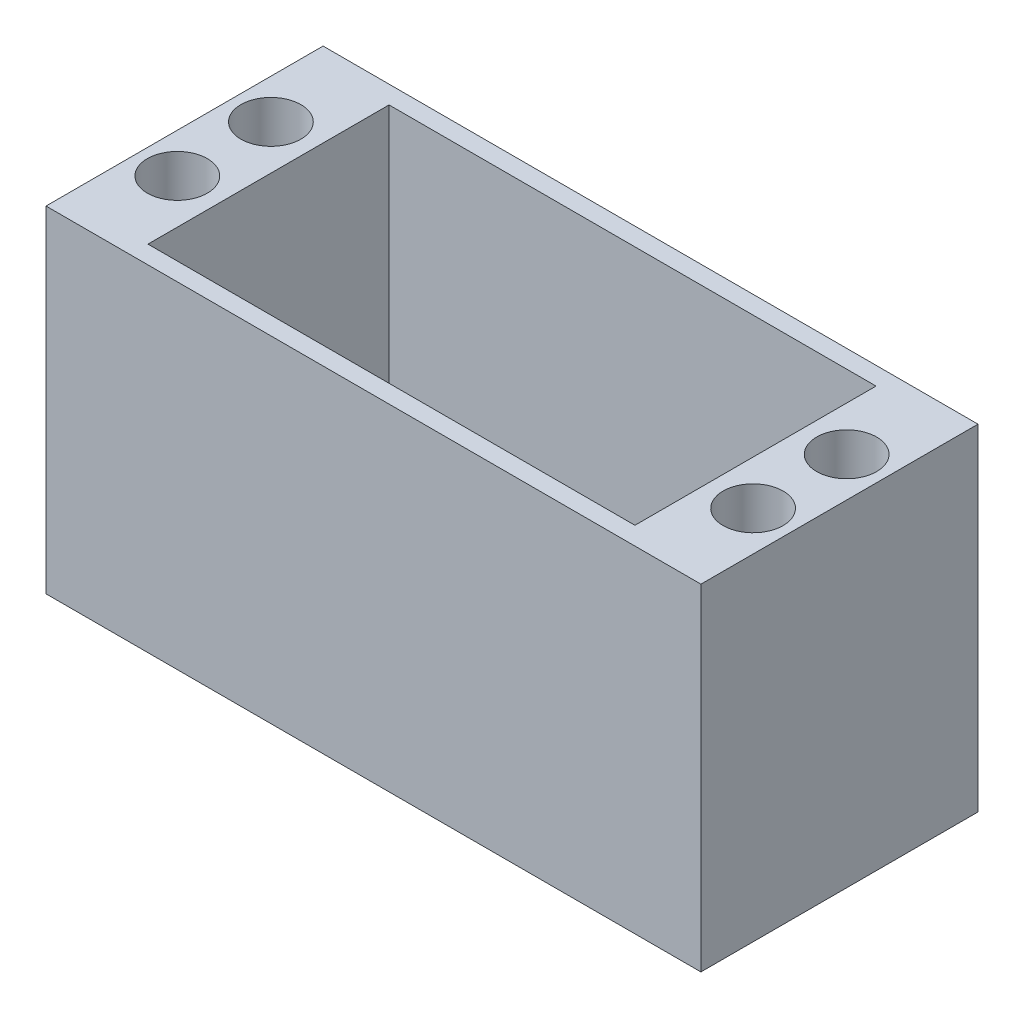
SolidWorks part; units mm, degrees
ref_plane "Front Plane" through (0, 0, 0) normal (0, 0, 1) x (1, 0, 0)
ref_plane "Top Plane" through (0, 0, 0) normal (0, 1, 0) x (1, 0, 0)
ref_plane "Right Plane" through (0, 0, 0) normal (1, 0, 0) x (0, 0, -1)
sketch "Sketch2" plane through (0, 0, 0) normal (0, 1, 0) x (1, 0, 0)
  line L1 (-20.3, 10.05) -> (20.3, 10.05)
  line L2 (-20.3, 10.05) -> (-20.3, -10.05)
  line L3 (-20.3, -10.05) -> (20.3, -10.05)
  line L4 (20.3, 10.05) -> (20.3, -10.05)
  line L5 (-20.3, 10.05) -> (20.3, -10.05) construction
  line L6 (-20.3, -10.05) -> (20.3, 10.05) construction
  line L7 (27.3, -11.55) -> (-27.3, -11.55)
  line L8 (27.3, -11.55) -> (27.3, 11.55)
  line L9 (27.3, 11.55) -> (-27.3, 11.55)
  line L10 (-27.3, -11.55) -> (-27.3, 11.55)
  line L11 (27.3, -11.55) -> (-27.3, 11.55) construction
  line L12 (27.3, 11.55) -> (-27.3, -11.55) construction
  point P0 (0, 0)
  point P6 (0, 0)
  dimension "D1" = 20.1
  dimension "D2" = 40.6
  dimension "D3" = 54.6
  dimension "D4" = 1.5
extrude "Boss-Extrude2" add sketch "Sketch2" along normal blind 28
sketch "Sketch3" plane through (0, 28, 0) normal (0, 1, 0) x (1, 0, 0)
  circle A0 centre (-24, 3.9) radius 2.5
  circle A1 centre (24, 3.9) radius 2.5
  circle A2 centre (24, -3.9) radius 2.5
  circle A3 centre (-24, -3.9) radius 2.5
  dimension "D7" = 5
  dimension "D1" = 7.8
  dimension "D2" = 3.9
  dimension "D3" = 7.8
  dimension "D4" = 3.9
  dimension "D5" = 48
  dimension "D6" = 24
extrude "Cut-Extrude1" cut sketch "Sketch3" against normal through all
